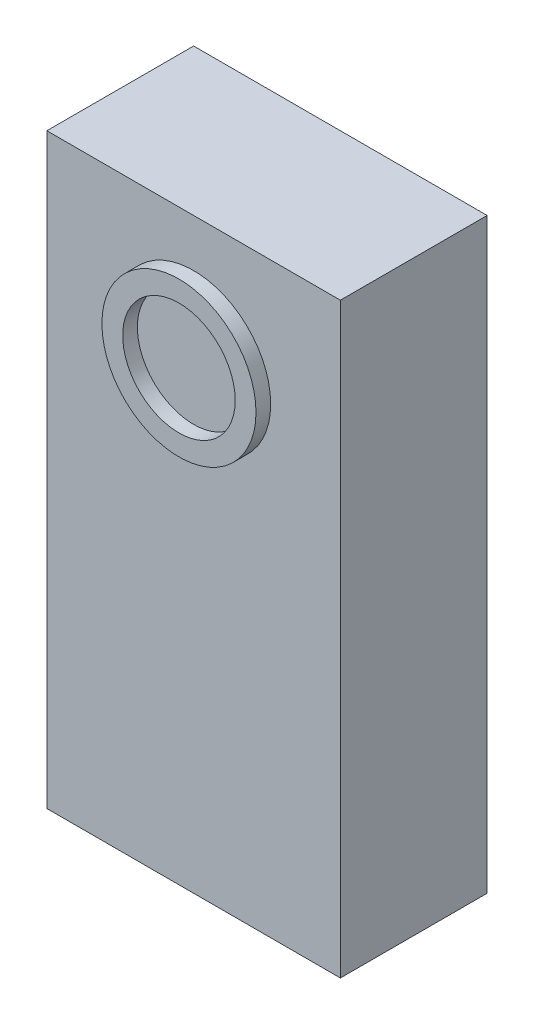
SolidWorks part; units mm, degrees
ref_plane "Front Plane" through (0, 0, 0) normal (0, 0, 1) x (1, 0, 0)
ref_plane "Top Plane" through (0, 0, 0) normal (0, 1, 0) x (1, 0, 0)
ref_plane "Right Plane" through (0, 0, 0) normal (1, 0, 0) x (0, 0, -1)
sketch "Sketch1" plane through (0, 0, 0) normal (0, 0, 1) x (1, 0, 0)
  line L1 (-1, 2) -> (1, 2)
  line L2 (-1, 2) -> (-1, -2)
  line L3 (-1, -2) -> (1, -2)
  line L4 (1, 2) -> (1, -2)
  line L5 (-1, 2) -> (1, -2) construction
  line L6 (-1, -2) -> (1, 2) construction
  point P0 (0, 0)
extrude "Boss-Extrude1" add sketch "Sketch1" along normal blind 1
sketch "Sketch2" plane through (0, 0, 1) normal (0, 0, 1) x (1, 0, 0)
  line L0 (1, 2) -> (-1, 2) construction
  circle A0 centre (0, 1.15) radius 0.525
  circle A1 centre (0, 1.15) radius 0.3834
  dimension "D1" = 0.85
extrude "Boss-Extrude2" add sketch "Sketch2" along normal blind 0.1
